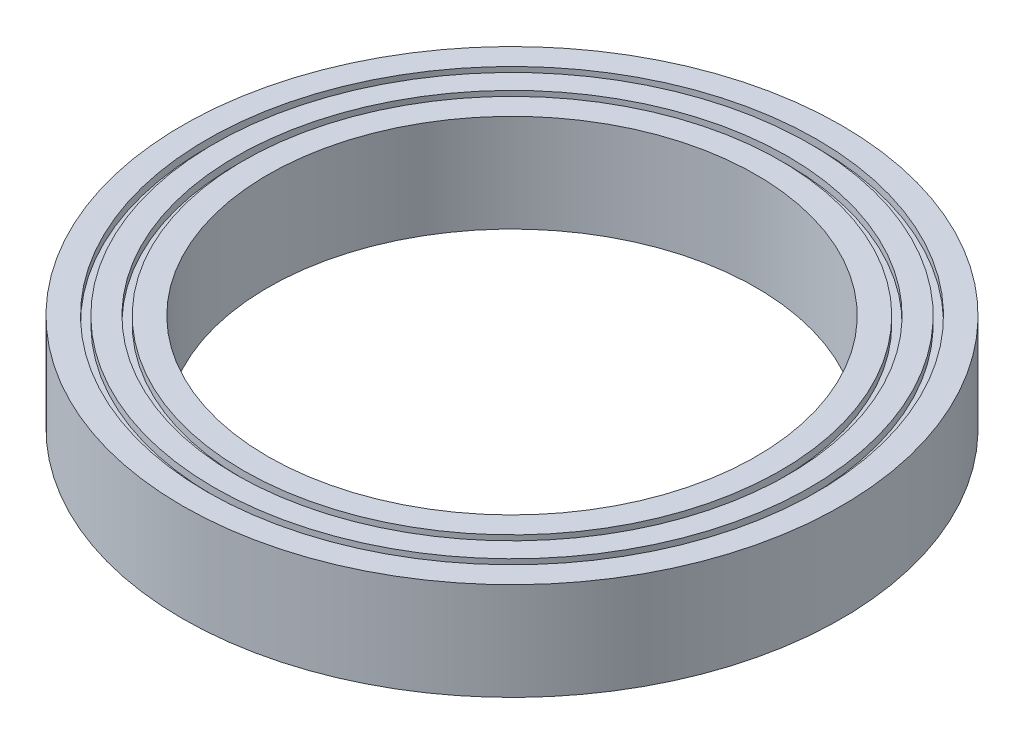
SolidWorks part; units mm, degrees
ref_plane "前视基准面" through (0, 0, 0) normal (0, 0, 1) x (1, 0, 0)
ref_plane "上视基准面" through (0, 0, 0) normal (0, 1, 0) x (1, 0, 0)
ref_plane "右视基准面" through (0, 0, 0) normal (1, 0, 0) x (0, 0, -1)
sketch "草图1" plane through (0, 0, 0) normal (0, 1, 0) x (1, 0, 0)
  circle A0 centre (0, 0) radius 13.5
  circle A1 centre (0, 0) radius 10
  dimension "D1" = 27
  dimension "D2" = 20
extrude "凸台-拉伸1" add sketch "草图1" along normal blind 4
sketch "草图2" plane through (0, 4, 0) normal (0, 1, 0) x (1, 0, 0)
  circle A0 centre (0, 0) radius 11
  circle A1 centre (0, 0) radius 11.3
  circle A2 centre (0, 0) radius 12.2
  circle A3 centre (0, 0) radius 12.5
  circle A4 centre (0, 0) radius 10 construction
  circle A5 centre (0, 0) radius 13.5 construction
  dimension "D1" = 0.3
  dimension "D2" = 0.3
  dimension "D3" = 1
  dimension "D4" = 1
extrude "切除-拉伸1" cut sketch "草图2" against normal blind 0.3 contours A3 A2 | A1 A0
ref_plane "基准面1" through (0, 2, 0) normal (0, 1, 0) x (1, 0, 0)
mirror "镜向1" about plane through (0, 2, 0) normal (0, 1, 0) of "切除-拉伸1"
